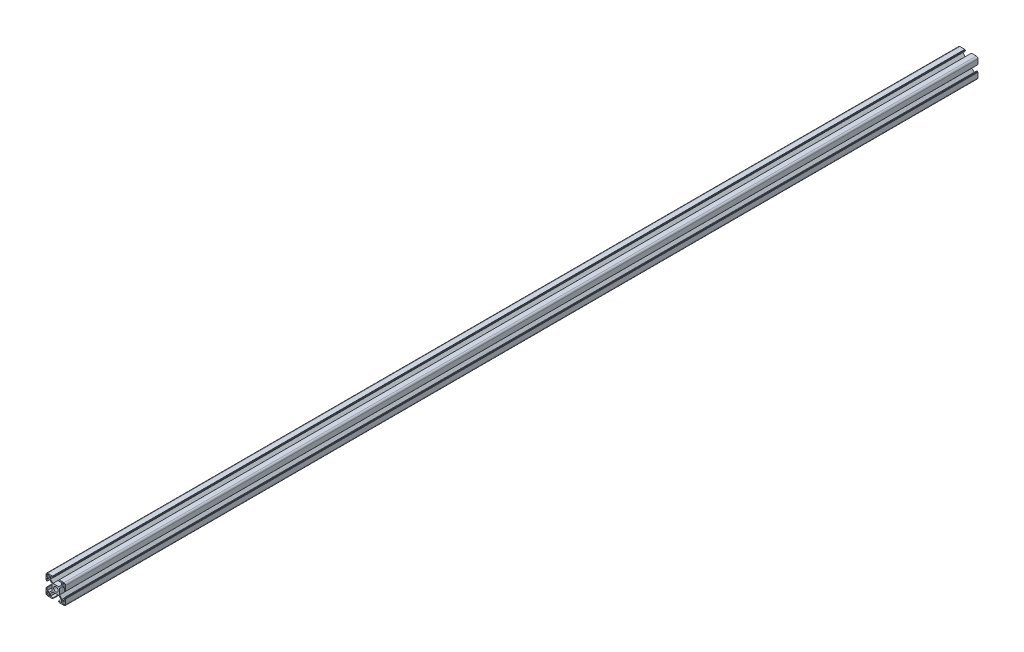
SolidWorks part; units mm, degrees
material "6061-T6 (SS)"
ref_plane "前视基准面" through (0, 0, 0) normal (0, 0, 1) x (1, 0, 0)
ref_plane "上视基准面" through (0, 0, 0) normal (0, 1, 0) x (1, 0, 0)
ref_plane "右视基准面" through (0, 0, 0) normal (1, 0, 0) x (0, 0, -1)
sketch "Sketch1" plane through (0, 0, 0) normal (0, 0, 1) x (1, 0, 0)
  line L0 (-5.1, 15) -> (-5.1, 14.2)
  line L1 (-12.5, -15) -> (12.5, -15)
  line L2 (-15, -12.5) -> (-15, 12.5)
  line L3 (-12.5, 15) -> (12.5, 15)
  line L4 (15, -12.5) -> (15, 12.5)
  line L5 (-15, -15) -> (15, 15) construction
  line L6 (-15, 15) -> (15, -15) construction
  line L7 (-5.1, 14.2) -> (-4.1, 14.2)
  line L8 (-4.1, 14.2) -> (-4.1, 13.2)
  line L9 (-4.1, 13.2) -> (-8.25, 13.2)
  line L10 (-8.25, 13.2) -> (-8.25, 9.5228)
  line L11 (-8.25, 9.5228) -> (-4.4272, 5.7)
  line L12 (-4.4272, 5.7) -> (4.4272, 5.7)
  line L13 (-5.1, 15) -> (5.1, 15)
  line L14 (0, 15) -> (0, 5.7) construction
  line L15 (8.25, 9.5228) -> (4.4272, 5.7)
  line L16 (8.25, 13.2) -> (8.25, 9.5228)
  line L17 (4.1, 13.2) -> (8.25, 13.2)
  line L18 (4.1, 14.2) -> (4.1, 13.2)
  line L19 (5.1, 14.2) -> (4.1, 14.2)
  line L20 (5.1, 15) -> (5.1, 14.2)
  line L21 (15, 5.1) -> (14.2, 5.1)
  line L22 (14.2, 5.1) -> (14.2, 4.1)
  line L23 (14.2, 4.1) -> (13.2, 4.1)
  line L24 (13.2, 4.1) -> (13.2, 8.25)
  line L25 (13.2, 8.25) -> (9.5228, 8.25)
  line L26 (9.5228, 8.25) -> (5.7, 4.4272)
  line L27 (5.7, 4.4272) -> (5.7, -4.4272)
  line L28 (15, 5.1) -> (15, -5.1)
  line L29 (9.5228, -8.25) -> (5.7, -4.4272)
  line L30 (13.2, -8.25) -> (9.5228, -8.25)
  line L31 (13.2, -4.1) -> (13.2, -8.25)
  line L32 (14.2, -4.1) -> (13.2, -4.1)
  line L33 (14.2, -5.1) -> (14.2, -4.1)
  line L34 (15, -5.1) -> (14.2, -5.1)
  line L35 (15, 0) -> (5.7, 0) construction
  line L36 (5.1, -15) -> (5.1, -14.2)
  line L37 (5.1, -14.2) -> (4.1, -14.2)
  line L38 (4.1, -14.2) -> (4.1, -13.2)
  line L39 (4.1, -13.2) -> (8.25, -13.2)
  line L40 (8.25, -13.2) -> (8.25, -9.5228)
  line L41 (8.25, -9.5228) -> (4.4272, -5.7)
  line L42 (4.4272, -5.7) -> (-4.4272, -5.7)
  line L43 (5.1, -15) -> (-5.1, -15)
  line L44 (-8.25, -9.5228) -> (-4.4272, -5.7)
  line L45 (-8.25, -13.2) -> (-8.25, -9.5228)
  line L46 (-4.1, -13.2) -> (-8.25, -13.2)
  line L47 (-4.1, -14.2) -> (-4.1, -13.2)
  line L48 (-5.1, -14.2) -> (-4.1, -14.2)
  line L49 (-5.1, -15) -> (-5.1, -14.2)
  line L50 (0, -15) -> (0, -5.7) construction
  line L51 (-15, -5.1) -> (-14.2, -5.1)
  line L52 (-14.2, -5.1) -> (-14.2, -4.1)
  line L53 (-14.2, -4.1) -> (-13.2, -4.1)
  line L54 (-13.2, -4.1) -> (-13.2, -8.25)
  line L55 (-13.2, -8.25) -> (-9.5228, -8.25)
  line L56 (-9.5228, -8.25) -> (-5.7, -4.4272)
  line L57 (-5.7, -4.4272) -> (-5.7, 4.4272)
  line L58 (-15, -5.1) -> (-15, 5.1)
  line L59 (-9.5228, 8.25) -> (-5.7, 4.4272)
  line L60 (-13.2, 8.25) -> (-9.5228, 8.25)
  line L61 (-13.2, 4.1) -> (-13.2, 8.25)
  line L62 (-14.2, 4.1) -> (-13.2, 4.1)
  line L63 (-14.2, 5.1) -> (-14.2, 4.1)
  line L64 (-15, 5.1) -> (-14.2, 5.1)
  line L65 (-15, 0) -> (-5.7, 0) construction
  line L66 (0, 0) -> (0, 5.7) construction
  circle A0 centre (0, 0) radius 3.4
  arc A1 (-12.5, -15) -> (-15, -12.5) centre (-12.5, -12.5) cw
  arc A2 (12.5, -15) -> (15, -12.5) centre (12.5, -12.5) ccw
  arc A3 (12.5, 15) -> (15, 12.5) centre (12.5, 12.5) cw
  arc A4 (-15, 12.5) -> (-12.5, 15) centre (-12.5, 12.5) cw
  point P0 (0, 0)
  dimension "D3" = 6.8
  dimension "D12" = 2.5
  dimension "D1" = 30
  dimension "D2" = 30
  dimension "D4" = 16.5
  dimension "D5" = 8.2
  dimension "D6" = 10.2
  dimension "D7" = 7.5
  dimension "D9" = 1.8
  dimension "D10" = 1.8
  dimension "D11" = 0.8
  dimension "D8" = 4
extrude "Extrude1" add sketch "Sketch1" along normal blind 1390 contours A4 L2 L64 L63 L62 L61 L60 L59 L57 L56 L55 L54 L53 L52 L51 A1 L1 L49 L48 L47 L46 L45 L44 L42 L41 L40 L39 L38 L37 L36 A2 L4 L34 L33 L32 L31 L30 L29 L27 L26 L25 L24 L23 L22 L21 A3 L3 L20
sketch "Sketch2" plane through (0, 0, 1390) normal (0, 0, 1) x (1, 0, 0)
  line L0 (13.7, 12.7) -> (13.7, 10.55)
  line L1 (-12.7, 13.7) -> (-10.55, 13.7)
  line L2 (-13.7, 12.7) -> (-13.7, 10.55)
  line L3 (-12.7, 9.55) -> (-10.55, 9.55)
  line L4 (-9.55, 12.7) -> (-9.55, 10.55)
  line L5 (-13.7, 13.7) -> (-9.55, 9.55) construction
  line L6 (-13.7, 9.55) -> (-9.55, 13.7) construction
  line L7 (12.7, 13.7) -> (10.55, 13.7)
  line L8 (9.55, 12.7) -> (9.55, 10.55)
  line L9 (12.7, 9.55) -> (10.55, 9.55)
  line L10 (12.7, -13.7) -> (10.55, -13.7)
  line L11 (13.7, -12.7) -> (13.7, -10.55)
  line L12 (12.7, -9.55) -> (10.55, -9.55)
  line L13 (9.55, -12.7) -> (9.55, -10.55)
  line L14 (-13.7, -12.7) -> (-13.7, -10.55)
  line L15 (-12.7, -13.7) -> (-10.55, -13.7)
  line L16 (-9.55, -12.7) -> (-9.55, -10.55)
  line L17 (-12.7, -9.55) -> (-10.55, -9.55)
  line L18 (0, 0) -> (-9.55, 9.55) construction
  line L19 (-12.5, 15) -> (-5.1, 15) construction
  line L20 (-15, 5.1) -> (-15, 12.5) construction
  line L21 (-13.2, 8.25) -> (-9.5228, 8.25) construction
  line L22 (-8.25, 13.2) -> (-8.25, 9.5228) construction
  arc A0 (-13.7, -12.7) -> (-12.7, -13.7) centre (-12.7, -12.7) ccw
  arc A1 (-10.55, -13.7) -> (-9.55, -12.7) centre (-10.55, -12.7) ccw
  arc A2 (-9.55, -10.55) -> (-10.55, -9.55) centre (-10.55, -10.55) ccw
  arc A3 (-13.7, -10.55) -> (-12.7, -9.55) centre (-12.7, -10.55) cw
  arc A4 (13.7, -10.55) -> (12.7, -9.55) centre (12.7, -10.55) ccw
  arc A5 (12.7, -13.7) -> (13.7, -12.7) centre (12.7, -12.7) ccw
  arc A6 (10.55, -13.7) -> (9.55, -12.7) centre (10.55, -12.7) cw
  arc A7 (10.55, -9.55) -> (9.55, -10.55) centre (10.55, -10.55) ccw
  arc A8 (13.7, 12.7) -> (12.7, 13.7) centre (12.7, 12.7) ccw
  arc A9 (13.7, 10.55) -> (12.7, 9.55) centre (12.7, 10.55) cw
  arc A10 (9.55, 10.55) -> (10.55, 9.55) centre (10.55, 10.55) ccw
  arc A11 (10.55, 13.7) -> (9.55, 12.7) centre (10.55, 12.7) ccw
  arc A12 (-10.55, 13.7) -> (-9.55, 12.7) centre (-10.55, 12.7) cw
  arc A13 (-10.55, 9.55) -> (-9.55, 10.55) centre (-10.55, 10.55) ccw
  arc A14 (-13.7, 10.55) -> (-12.7, 9.55) centre (-12.7, 10.55) ccw
  arc A15 (-12.7, 13.7) -> (-13.7, 12.7) centre (-12.7, 12.7) ccw
  point P0 (-11.625, 11.625)
  dimension "D2" = 1
  dimension "D3" = 1.3
  dimension "D4" = 1.3
  dimension "D5" = 1.3
  dimension "D6" = 1.3
  dimension "D1" = 4
extrude "Extrude2" cut sketch "Sketch2" against normal through all
